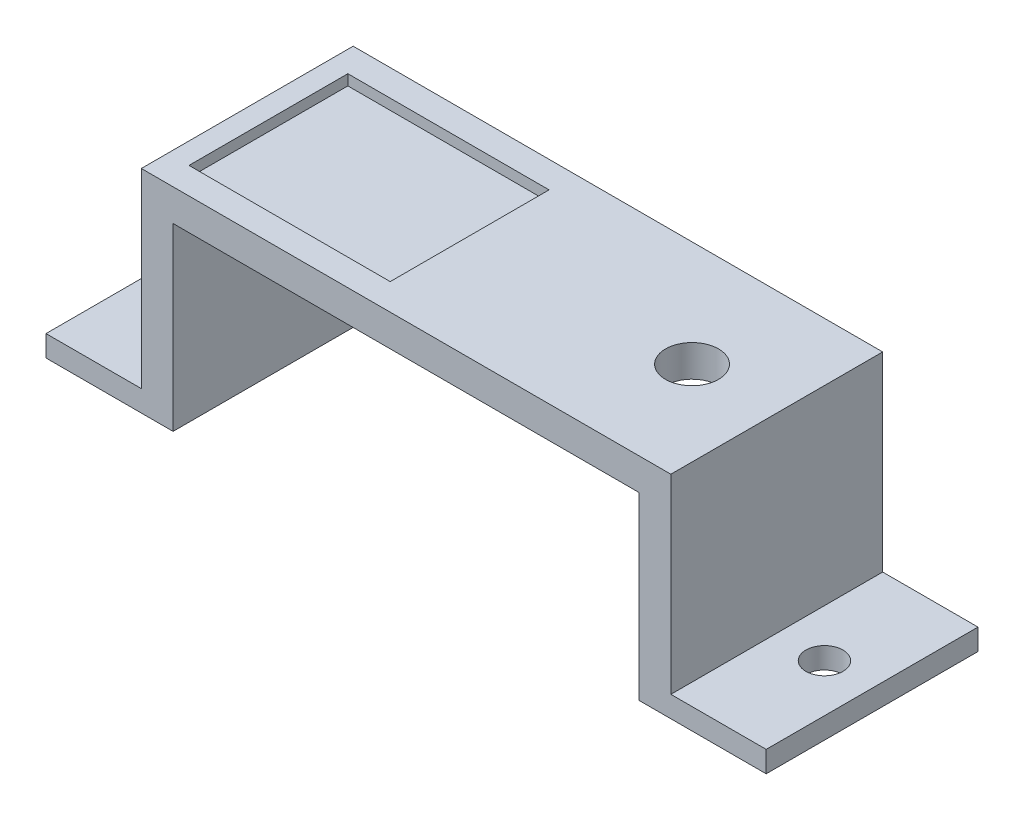
SolidWorks part; units mm, degrees
ref_plane "Front Plane" through (0, 0, 0) normal (0, 0, 1) x (1, 0, 0)
ref_plane "Top Plane" through (0, 0, 0) normal (0, 1, 0) x (1, 0, 0)
ref_plane "Right Plane" through (0, 0, 0) normal (1, 0, 0) x (0, 0, -1)
sketch "Sketch1" plane through (0, 0, 0) normal (0, 0, 1) x (1, 0, 0)
  line L6 (22, 0) -> (22, 17)
  line L7 (22, 17) -> (-22, 17)
  line L8 (-22, 0) -> (-22, 17)
  line L9 (-25, 0) -> (-22, 0)
  line L10 (22, 0) -> (25, 0)
  line L12 (25, 0) -> (25, 20)
  line L13 (25, 20) -> (-25, 20)
  line L14 (-25, 0) -> (-25, 20)
  line L15 (0, 34) -> (0, 0) construction
  point P2 (0, 17)
  dimension "D1" = 3
  dimension "D2" = 20
  dimension "D3" = 3
  dimension "D4" = 50
extrude "Boss-Extrude1" add sketch "Sketch1" along normal blind 20
sketch "Sketch2" plane through (0, 20, 0) normal (0, 1, 0) x (1, 0, 0)
  line L0 (-25, -20) -> (-25, 0) construction
  line L1 (-23, -17.5) -> (-4, -17.5)
  line L2 (-23, -17.5) -> (-23, -2.5)
  line L3 (-23, -2.5) -> (-4, -2.5)
  line L4 (-4, -17.5) -> (-4, -2.5)
  line L5 (-23, -17.5) -> (-4, -2.5) construction
  line L6 (-23, -2.5) -> (-4, -17.5) construction
  point P0 (-13.5, -10)
  point P9 (-25, -10)
  dimension "D1" = 15
  dimension "D2" = 19
  dimension "D3" = 2
extrude "Cut-Extrude1" cut sketch "Sketch2" against normal blind 1
sketch "Sketch3" plane through (0, 20, 0) normal (0, 1, 0) x (1, 0, 0)
  line L0 (-4, -17.5) -> (-4, -2.5) construction
  line L1 (-23, -2.5) -> (-23, -17.5) construction
  circle A0 centre (17, -10) radius 2.5
  point P5 (-4, -10)
  dimension "D2" = 5
  dimension "D1" = 40
extrude "Cut-Extrude2" cut sketch "Sketch3" against normal through all contours A0
sketch "Sketch4" plane through (0, 0, 0) normal (0, -1, 0) x (1, 0, 0)
  line L0 (-25, 20) -> (-25, 0) construction
  line L1 (-34, 0) -> (-25, 0)
  line L2 (-34, 0) -> (-34, 20)
  line L3 (-34, 20) -> (-25, 20)
  line L4 (-25, 0) -> (-25, 20)
  line L5 (-34, 0) -> (-25, 20) construction
  line L6 (-34, 20) -> (-25, 0) construction
  line L7 (25, 20) -> (25, 0) construction
  line L8 (34, 0) -> (25, 0)
  line L9 (34, 0) -> (34, 20)
  line L10 (34, 20) -> (25, 20)
  line L11 (25, 0) -> (25, 20)
  line L12 (34, 0) -> (25, 20) construction
  line L13 (34, 20) -> (25, 0) construction
  line L14 (-22, 20) -> (-22, 0) construction
  point P0 (-29.5, 10)
  point P7 (29.5, 10)
  point P16 (-22, 10)
  dimension "D2" = 9
extrude "Boss-Extrude2" add sketch "Sketch4" against normal blind 2
sketch "Sketch5" plane through (0, 0, 0) normal (0, -1, 0) x (1, 0, 0)
  line L0 (0, 30.289) -> (0, -14.3575) construction
  line L2 (-34, 20) -> (-34, 0) construction
  line L4 (-34, 0) -> (-25, 0) construction
  circle A0 centre (-29.5, 10) radius 1.75
  circle A1 centre (29.5, 10) radius 1.75
  point P7 (-29.2079, 10)
  point P10 (-34, 10)
  point P11 (-16.948, 10)
  point P12 (-29.4163, 10)
  point P16 (0, 0)
  point P19 (-29.5, 0)
  dimension "D1" = 3.5
extrude "Cut-Extrude3" cut sketch "Sketch5" against normal through all
